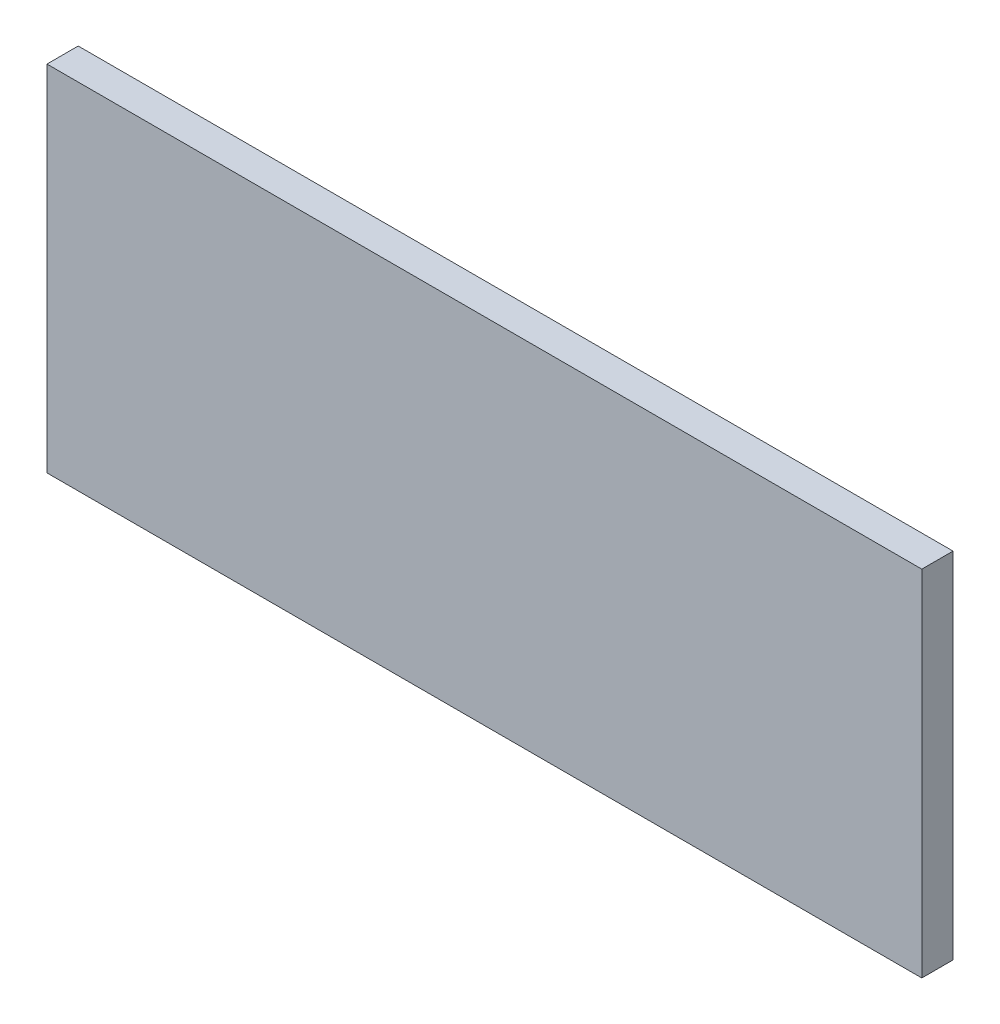
SolidWorks part; units mm, degrees
ref_plane "Front Plane" through (0, 0, 0) normal (0, 0, 1) x (1, 0, 0)
ref_plane "Top Plane" through (0, 0, 0) normal (0, 1, 0) x (1, 0, 0)
ref_plane "Right Plane" through (0, 0, 0) normal (1, 0, 0) x (0, 0, -1)
sketch "Sketch1" plane through (0, 0, 0) normal (0, 0, 1) x (1, 0, 0)
  line L1 (-84, -34) -> (84, -34)
  line L2 (-84, -34) -> (-84, 34)
  line L3 (-84, 34) -> (84, 34)
  line L4 (84, -34) -> (84, 34)
  line L5 (-84, -34) -> (84, 34) construction
  line L6 (-84, 34) -> (84, -34) construction
  point P0 (0, 0)
  dimension "D1" = 68
  dimension "D2" = 168
extrude "Boss-Extrude1" add sketch "Sketch1" along normal blind 6
